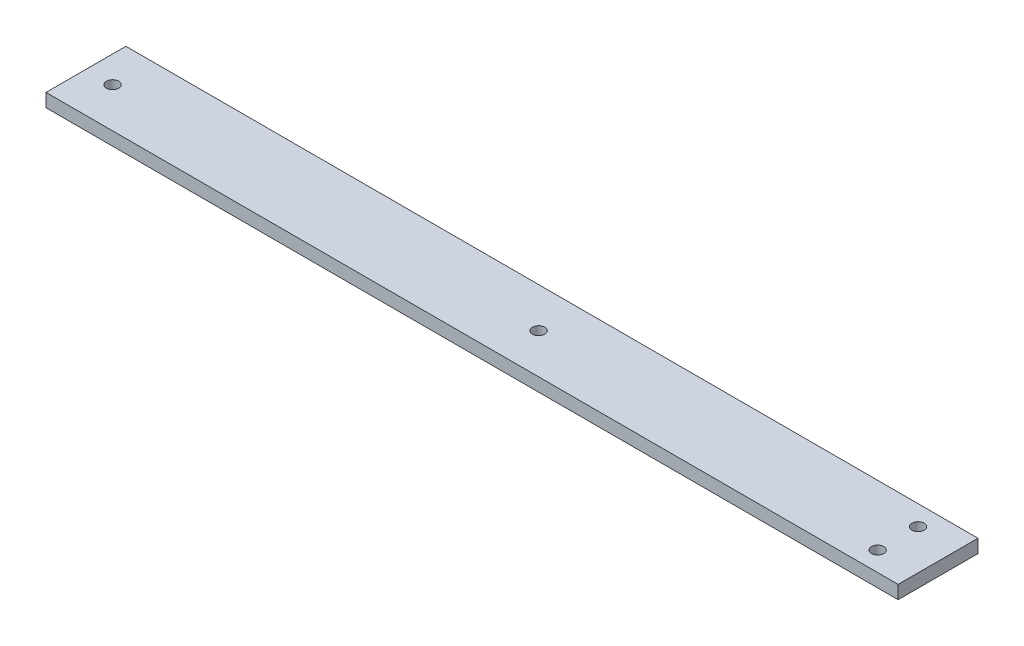
SolidWorks part; units mm, degrees
ref_plane "Front Plane" through (0, 0, 0) normal (0, 0, 1) x (1, 0, 0)
ref_plane "Top Plane" through (0, 0, 0) normal (0, 1, 0) x (1, 0, 0)
ref_plane "Right Plane" through (0, 0, 0) normal (1, 0, 0) x (0, 0, -1)
sketch "Sketch1" plane through (0, 0, 0) normal (0, 1, 0) x (1, 0, 0)
  line L1 (0, 0) -> (203.2, 0)
  line L2 (0, 0) -> (0, 19.05)
  line L3 (0, 19.05) -> (203.2, 19.05)
  line L4 (203.2, 0) -> (203.2, 19.05)
  circle A0 centre (6.35, 9.525) radius 1.4605
  circle A1 centre (107.95, 9.525) radius 1.4605
  dimension "D3" = 2.921
  dimension "D6" = 2.921
  dimension "D8" = 107.95
  dimension "D1" = 203.2
  dimension "D2" = 19.05
  dimension "D4" = 6.35
  dimension "D5" = 9.525
  dimension "D7" = 9.525
extrude "Boss-Extrude1" add sketch "Sketch1" along normal blind 3.175
sketch "Sketch2" plane through (0, 3.175, 0) normal (0, 1, 0) x (1, 0, 0)
  circle A0 centre (193.675, 14.2875) radius 1.4605
  circle A1 centre (193.675, 4.6355) radius 1.4605
  dimension "D1" = 2.921
  dimension "D2" = 2.921
extrude "Cut-Extrude1" cut sketch "Sketch2" against normal blind 9.525
